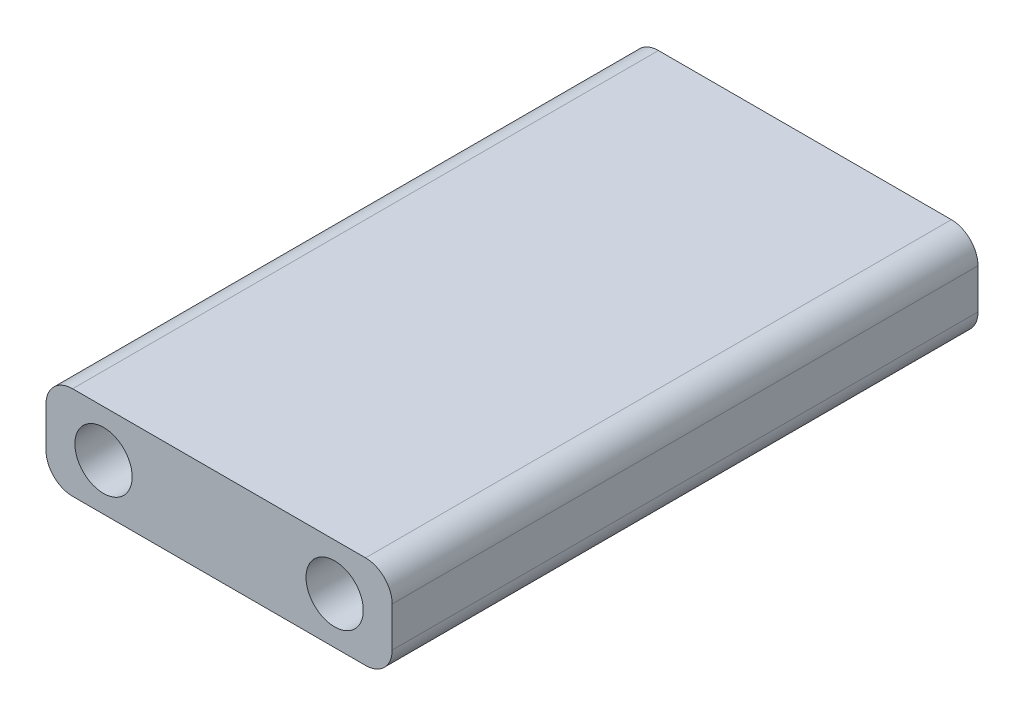
SolidWorks part; units mm, degrees
ref_plane "Płaszczyzna przednia" through (0, 0, 0) normal (0, 0, 1) x (1, 0, 0)
ref_plane "Płaszczyzna górna" through (0, 0, 0) normal (0, 1, 0) x (1, 0, 0)
ref_plane "Płaszczyzna prawa" through (0, 0, 0) normal (1, 0, 0) x (0, 0, -1)
sketch "Szkic1" plane through (0, 0, 0) normal (0, 1, 0) x (1, 0, 0)
  line L1 (-13, 22) -> (13, 22)
  line L2 (-13, 22) -> (-13, -22)
  line L3 (-13, -22) -> (13, -22)
  line L4 (13, 22) -> (13, -22)
  line L5 (-13, 22) -> (13, -22) construction
  line L6 (-13, -22) -> (13, 22) construction
  point P0 (0, 0)
  dimension "D1" = 44
  dimension "D2" = 26
extrude "Dodanie-wyciągnięcie1" add sketch "Szkic1" along normal blind 7
sketch "Szkic2" plane through (0, 0, 22) normal (0, 0, 1) x (1, 0, 0)
  line L0 (-8.68, 3.5) -> (-13, 3.5) construction
  line L1 (-13, 7) -> (-13, 0) construction
  line L2 (0, -55) -> (0, 55) construction
  circle A0 centre (-8.68, 3.5) radius 2.15
  circle A1 centre (8.68, 3.5) radius 2.15
  dimension "D2" = 4.3
  dimension "D1" = 4.32
extrude "Wytnij-wyciągnięcie1" cut sketch "Szkic2" against normal blind 5
mirror "Lustro1" about plane through (0, 0, 0) normal (0, 0, 1) of "Wytnij-wyciągnięcie1"
fillet "Zaokrąglenie1" radius 2 4 edges at (13, 0, 0) (-13, 0, 0) (13, 7, 0) (-13, 7, 0)
